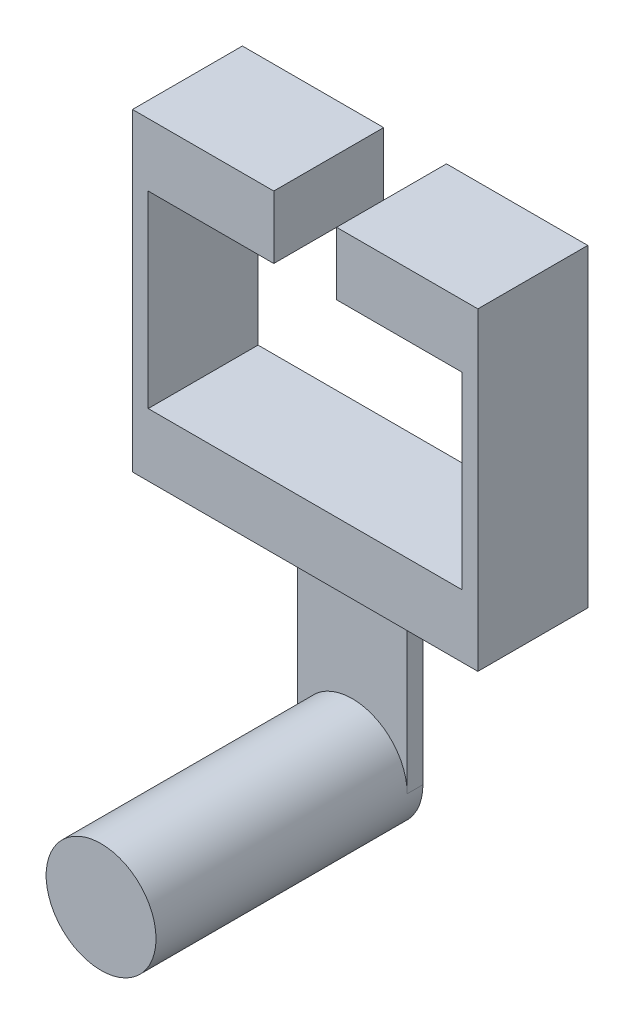
SolidWorks part; units mm, degrees
ref_plane "Front Plane" through (0, 0, 0) normal (0, 0, 1) x (1, 0, 0)
ref_plane "Top Plane" through (0, 0, 0) normal (0, 1, 0) x (1, 0, 0)
ref_plane "Right Plane" through (0, 0, 0) normal (1, 0, 0) x (0, 0, -1)
sketch "Sketch1" plane through (0, 0, 0) normal (0, 0, 1) x (1, 0, 0)
  line L0 (171.9051, 256.4856) -> (2921.9051, 256.4856)
  line L1 (2921.9051, 256.4856) -> (2921.9051, 2756.4856)
  line L2 (2921.9051, 2756.4856) -> (1796.9051, 2756.4856)
  line L3 (1796.9051, 2756.4856) -> (1796.9051, 2256.4856)
  line L4 (1796.9051, 2256.4856) -> (2796.9051, 2256.4856)
  line L5 (2796.9051, 2256.4856) -> (2796.9051, 756.4856)
  line L6 (2796.9051, 756.4856) -> (296.9051, 756.4856)
  line L7 (296.9051, 756.4856) -> (296.9051, 2256.4856)
  line L8 (296.9051, 2256.4856) -> (1296.9051, 2256.4856)
  line L9 (1296.9051, 2256.4856) -> (1296.9051, 2756.4856)
  line L10 (1296.9051, 2756.4856) -> (171.9051, 2756.4856)
  line L11 (171.9051, 256.4856) -> (171.9051, 2756.4856)
extrude "Boss-Extrude1" add sketch "Sketch1" along normal blind 875 contours L11 L10 L9 L8 L7 L6 L5 L4 L3 L2 L1 L0
sketch "Sketch2" plane through (0, 256.4856, 0) normal (0, -1, 0) x (-1, 0, 0)
  line L3 (-1109.4051, -500) -> (-1984.4051, -500)
  line L4 (-1984.4051, -500) -> (-1984.4051, -375)
  line L5 (-1984.4051, -375) -> (-1109.4051, -375)
  line L6 (-1109.4051, -375) -> (-1109.4051, -500)
extrude "Boss-Extrude2" add sketch "Sketch2" along normal blind 1500
sketch "Sketch3" plane through (0, 0, 500) normal (0, 0, 1) x (1, 0, 0)
  line L0 (1984.4051, -1243.5144) -> (1109.4051, -1243.5144) construction
  circle A0 centre (1546.9051, -1243.5144) radius 437.5
extrude "Boss-Extrude3" add sketch "Sketch3" along normal blind 2000
sketch "Sketch4" plane through (0, 0, 500) normal (0, 0, -1) x (-1, 0, 0)
  line L0 (-1109.4051, -1243.5144) -> (-1984.4051, -1243.5144) construction
  line L1 (-1984.4051, -1243.5144) -> (-1109.4051, -1243.5144)
  arc A0 (-1984.4051, -1243.5144) -> (-1109.4051, -1243.5144) centre (-1546.9051, -1243.5144) ccw
extrude "Boss-Extrude4" add sketch "Sketch4" along normal blind 125
